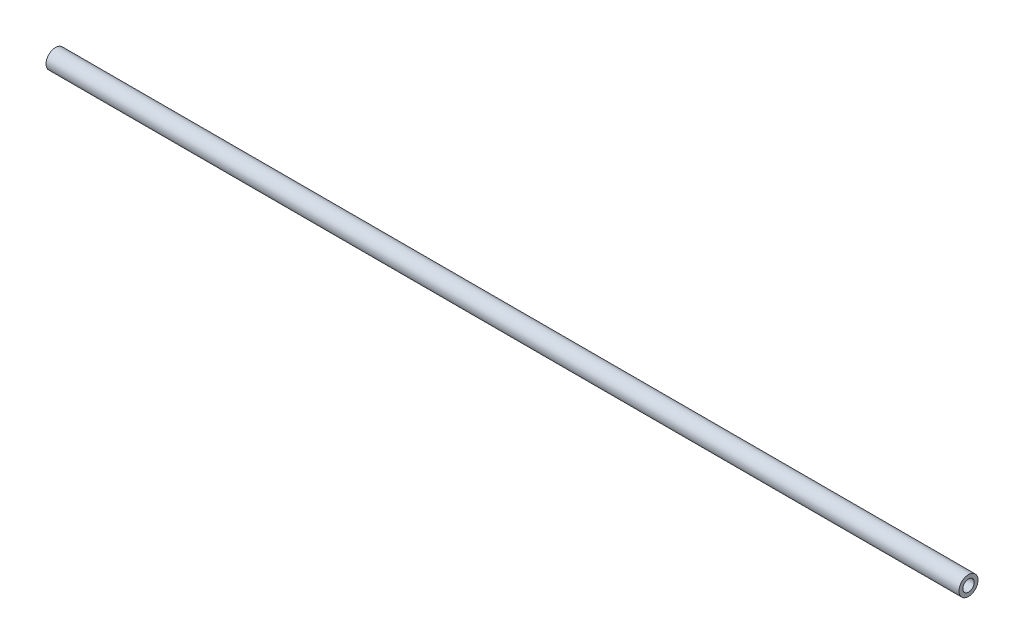
SolidWorks part; units mm, degrees
ref_plane "Front" through (0, 0, 0) normal (0, 0, 1) x (1, 0, 0)
ref_plane "Top" through (0, 0, 0) normal (0, 1, 0) x (1, 0, 0)
ref_plane "Right" through (0, 0, 0) normal (1, 0, 0) x (0, 0, -1)
sketch "Sketch1" plane through (0, 0, 0) normal (1, 0, 0) x (0, 0, -1)
  circle A0 centre (0, 0) radius 3.175
  circle A1 centre (0, 0) radius 1.905
  point P4 (3.175, 0)
  point P5 (1.905, 0)
  dimension "OD" = 6.35
  dimension "ID" = 3.81
  dimension "Wall" = 1.27
extrude "Extrude1" add sketch "Sketch1" along normal mid plane 304.8
